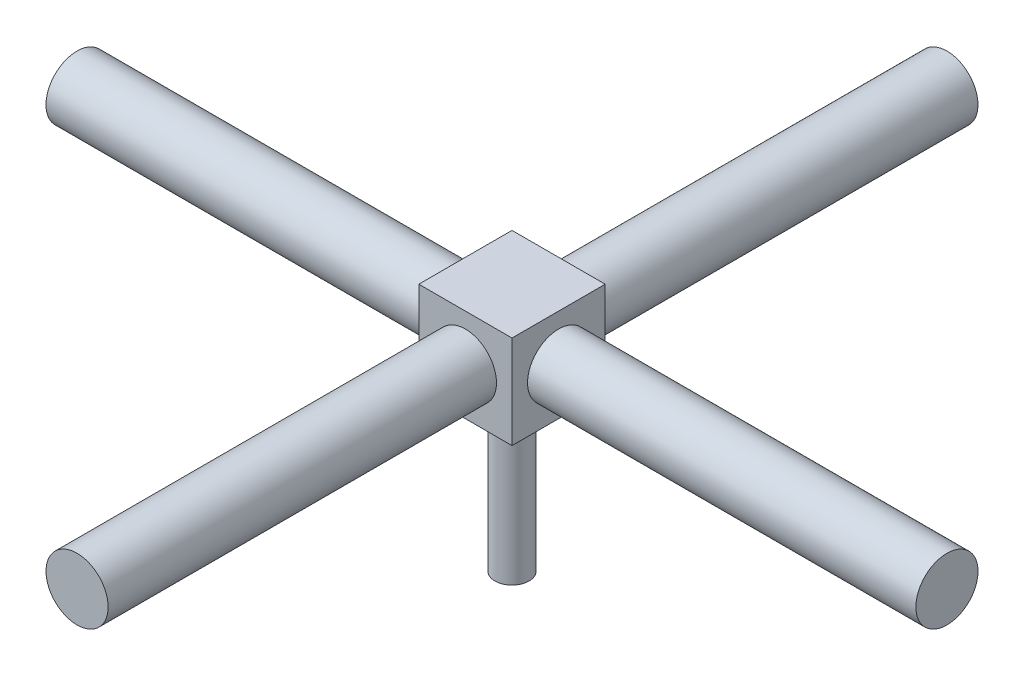
SolidWorks part; units mm, degrees
ref_plane "Front Plane" through (0, 0, 0) normal (0, 0, 1) x (1, 0, 0)
ref_plane "Top Plane" through (0, 0, 0) normal (0, 1, 0) x (1, 0, 0)
ref_plane "Right Plane" through (0, 0, 0) normal (1, 0, 0) x (0, 0, -1)
sketch "Sketch1" plane through (0, 0, 0) normal (0, 1, 0) x (1, 0, 0)
  line L1 (30, 30) -> (-30, 30)
  line L2 (30, 30) -> (30, -30)
  line L3 (30, -30) -> (-30, -30)
  line L4 (-30, 30) -> (-30, -30)
  line L5 (30, 30) -> (-30, -30) construction
  line L6 (30, -30) -> (-30, 30) construction
  point P0 (0, 0)
  dimension "D1" = 30
extrude "Boss-Extrude1" add sketch "Sketch1" along normal blind 60
sketch "Sketch2" plane through (0, 0, 30) normal (0, 0, 1) x (1, 0, 0)
  circle A0 centre (0, 30) radius 20
  dimension "D3" = 40
  dimension "D1" = 30
  dimension "D2" = 30
extrude "Boss-Extrude2" add sketch "Sketch2" along normal blind 250
sketch "Sketch3" plane through (-30, 0, 0) normal (-1, 0, 0) x (0, 0, 1)
  circle A0 centre (0, 30) radius 20
  dimension "D1" = 40
  dimension "D2" = 30
  dimension "D3" = 30
extrude "Boss-Extrude3" add sketch "Sketch3" along normal blind 250
sketch "Sketch4" plane through (0, 0, -30) normal (0, 0, -1) x (-1, 0, 0)
  circle A0 centre (0, 30) radius 20
  dimension "D1" = 40
  dimension "D2" = 30
  dimension "D3" = 30
extrude "Boss-Extrude4" add sketch "Sketch4" along normal blind 250
sketch "Sketch5" plane through (30, 0, 0) normal (1, 0, 0) x (0, 0, -1)
  line L0 (-30, 60) -> (-30, 0) construction
  circle A0 centre (0, 30) radius 20
  dimension "D2" = 40
  dimension "D1" = 30
  dimension "D3" = 30
extrude "Boss-Extrude5" add sketch "Sketch5" along normal blind 250
sketch "Sketch6" plane through (0, 0, 0) normal (0, -1, 0) x (1, 0, 0)
  circle A0 centre (0, 0) radius 11
  dimension "D1" = 22
extrude "Boss-Extrude6" add sketch "Sketch6" along normal blind 100
